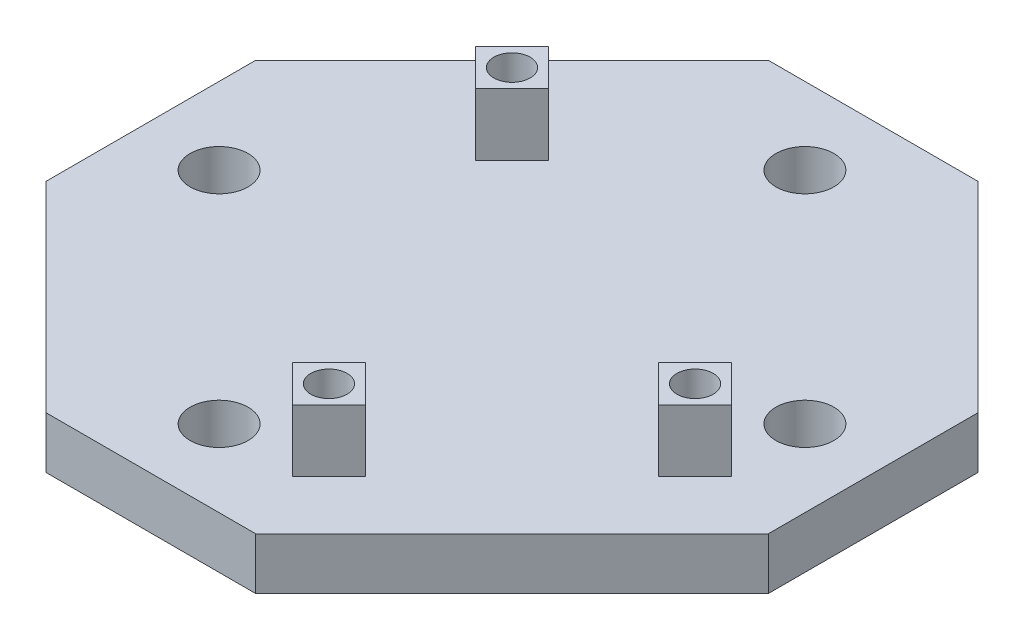
SolidWorks part; units mm, degrees
ref_plane "Front Plane" through (0, 0, 0) normal (0, 0, 1) x (1, 0, 0)
ref_plane "Top Plane" through (0, 0, 0) normal (0, 1, 0) x (1, 0, 0)
ref_plane "Right Plane" through (0, 0, 0) normal (1, 0, 0) x (0, 0, -1)
sketch "Sketch1" plane through (0, 0, 0) normal (0, 1, 0) x (1, 0, 0)
  line L0 (-40.3039, 15.5552) -> (-15.5552, 40.3039)
  line L1 (-40.3039, -40.3039) -> (40.3039, -40.3039) construction
  line L2 (-40.3039, -40.3039) -> (-40.3039, 40.3039) construction
  line L3 (-40.3039, 40.3039) -> (40.3039, 40.3039) construction
  line L4 (40.3039, -40.3039) -> (40.3039, 40.3039) construction
  line L5 (-40.3039, -40.3039) -> (40.3039, 40.3039) construction
  line L6 (-40.3039, 40.3039) -> (40.3039, -40.3039) construction
  line L7 (-27.9296, 27.9296) -> (2.476, -2.476) construction
  line L8 (-11.6661, -16.6182) -> (16.6182, 11.6661) construction
  line L9 (-11.6661, -16.6182) -> (-32.8793, 4.5951) construction
  line L10 (16.6182, 11.6661) -> (-4.5951, 32.8793) construction
  line L11 (-40.3039, 15.5552) -> (-40.3039, -4.6948)
  line L12 (-15.5552, 40.3039) -> (4.6948, 40.3039)
  line L13 (24.0428, 0.706) -> (24.0428, 20.956)
  line L14 (-0.706, -24.0428) -> (-20.956, -24.0428)
  line L15 (-32.8793, 4.5951) -> (-4.5951, 32.8793) construction
  line L16 (-18.7372, 18.7372) -> (11.6684, -11.6684) construction
  line L17 (-0.706, -24.0428) -> (24.0428, 0.706)
  line L18 (-40.3039, -4.6948) -> (-20.956, -24.0428)
  line L19 (4.6948, 40.3039) -> (24.0428, 20.956)
  circle A0 centre (-11.6661, -16.6182) radius 2.8
  circle A1 centre (16.6182, 11.6661) radius 2.8
  circle A2 centre (-4.5951, 32.8793) radius 2.8
  circle A3 centre (-32.8793, 4.5951) radius 2.8
  point P0 (0, 0)
  point P13 (2.476, -2.476)
  point P28 (11.6684, -11.6684)
  dimension "D6" = 5.6
  dimension "D1" = 135
  dimension "D2" = 35
  dimension "D3" = 43
  dimension "D4" = 40
  dimension "D5" = 30
  dimension "D7" = 20.25
  dimension "D8" = 20.25
  dimension "D9" = 43
  dimension "D10" = 35
  dimension "D11" = 20.25
  dimension "D12" = 20.25
extrude "Boss-Extrude1" add sketch "Sketch1" along normal blind 5
sketch "Sketch2" plane through (0, 5, 0) normal (0, 1, 0) x (1, 0, 0)
  line L0 (-27.9296, 27.9296) -> (11.6684, -11.6684) construction
  line L1 (-15.5552, 40.3039) -> (-40.3039, 15.5552) construction
  line L2 (-0.706, -24.0428) -> (24.0428, 0.706) construction
  line L3 (-18.7372, -2.476) -> (2.476, 18.7372) construction
  line L4 (-12.55, 33.7632) -> (17.502, 3.7112) construction
  line L5 (-12.55, 33.7632) -> (-33.7632, 12.55) construction
  line L6 (-33.7632, 12.55) -> (-3.7112, -17.502) construction
  line L7 (-3.7112, -17.502) -> (17.502, 3.7112) construction
  line L8 (15.7343, 5.4789) -> (13.9665, 3.7112) construction
  line L9 (13.9665, 3.7112) -> (15.7343, 1.9434) construction
  line L10 (-5.4789, -15.7343) -> (-3.7112, -13.9665) construction
  line L11 (-3.7112, -13.9665) -> (-1.9434, -15.7343) construction
  line L12 (-23.1566, 23.1566) -> (-21.3181, 21.3181) construction
  circle A0 centre (13.9665, 3.7112) radius 1.75
  circle A1 centre (-3.7112, -13.9665) radius 1.75
  circle A3 centre (-21.3181, 21.3181) radius 1.75
  point P9 (-8.1306, 8.1306)
  point P12 (2.476, 18.7372)
  dimension "D7" = 3.5
  dimension "D10" = 3.5
  dimension "D11" = 2.6
  dimension "D12" = 3.5
  dimension "D1" = 30
  dimension "D2" = 42.5
  dimension "D3" = 30
  dimension "D4" = 42.5
  dimension "D5" = 2.5
  dimension "D6" = 2.5
  dimension "D8" = 2.5
  dimension "D9" = 2.5
extrude "Cut-Extrude1" cut sketch "Sketch2" against normal blind 10 and the other way blind 16
sketch "Sketch3" plane through (0, 0, 0) normal (0, -1, 0) x (1, 0, 0)
  line L0 (-0.706, 24.0428) -> (24.0428, -0.706) construction
  line L1 (-4.5629, 10.7877) -> (-1.3842, 11.6395)
  line L2 (-1.3842, 11.6395) -> (-0.5324, 14.8182)
  line L3 (-0.5324, 14.8182) -> (-2.8594, 17.1453)
  line L4 (-2.8594, 17.1453) -> (-6.0382, 16.2935)
  line L5 (-6.0382, 16.2935) -> (-6.8899, 13.1148)
  line L6 (-6.8899, 13.1148) -> (-4.5629, 10.7877)
  line L7 (10.7877, -4.5629) -> (13.1148, -6.8899)
  line L8 (13.1148, -6.8899) -> (16.2935, -6.0382)
  line L9 (16.2935, -6.0382) -> (17.1453, -2.8594)
  line L10 (17.1453, -2.8594) -> (14.8182, -0.5324)
  line L11 (14.8182, -0.5324) -> (11.6395, -1.3842)
  line L12 (11.6395, -1.3842) -> (10.7877, -4.5629)
  line L13 (-22.1699, -24.4969) -> (-18.9911, -23.6451)
  line L14 (-18.9911, -23.6451) -> (-18.1394, -20.4664)
  line L15 (-18.1394, -20.4664) -> (-20.4664, -18.1394)
  line L16 (-20.4664, -18.1394) -> (-23.6451, -18.9911)
  line L17 (-23.6451, -18.9911) -> (-24.4969, -22.1699)
  line L18 (-24.4969, -22.1699) -> (-22.1699, -24.4969)
  line L19 (-15.5552, -40.3039) -> (-40.3039, -15.5552) construction
  circle A0 centre (-3.7112, 13.9665) radius 2.85 construction
  circle A1 centre (13.9665, -3.7112) radius 2.85 construction
  circle A2 centre (-21.3181, -21.3181) radius 2.85 construction
  dimension "D1" = 5.7
extrude "Cut-Extrude2" cut sketch "Sketch3" against normal blind 3.5
sketch "Sketch4" plane through (0, 5, 0) normal (0, 1, 0) x (1, 0, 0)
  line L0 (-5.4789, -15.7343) -> (-1.9434, -12.1987) construction
  line L1 (-0.706, -24.0428) -> (24.0428, 0.706) construction
  line L2 (-7.2467, -13.9665) -> (-3.7112, -17.502)
  line L3 (-3.7112, -10.431) -> (-0.1756, -13.9665)
  line L4 (-7.2467, -13.9665) -> (-3.7112, -10.431)
  line L5 (-3.7112, -17.502) -> (-0.1756, -13.9665)
  line L6 (-23.0859, 19.5504) -> (-19.5504, 23.0859) construction
  line L7 (-12.55, 33.7632) -> (-33.7632, 12.55) construction
  line L8 (-21.3181, 17.7826) -> (-24.8537, 21.3181)
  line L9 (-40.3039, -4.6948) -> (-20.956, -24.0428) construction
  line L10 (-17.7826, 21.3181) -> (-21.3181, 24.8537)
  line L11 (-24.8537, 21.3181) -> (-21.3181, 24.8537)
  line L12 (-21.3181, 17.7826) -> (-17.7826, 21.3181)
  line L13 (12.1987, 5.4789) -> (15.7343, 1.9434) construction
  line L14 (10.431, 3.7112) -> (13.9665, 7.2467)
  line L15 (17.502, 3.7112) -> (13.9665, 0.1756)
  line L16 (10.431, 3.7112) -> (13.9665, 0.1756)
  line L17 (13.9665, 7.2467) -> (17.502, 3.7112)
  point P4 (-3.7112, -13.9665)
  point P9 (-5.4789, -15.7343)
  point P13 (-1.9434, -12.1987)
  point P17 (-21.3181, 21.3181)
  point P22 (-23.0859, 19.5504)
  point P27 (-19.5504, 23.0859)
  point P32 (13.9665, 3.7112)
  point P36 (12.1987, 5.4789)
  point P39 (15.7343, 1.9434)
  dimension "D1" = 5
  dimension "D2" = 5
  dimension "D3" = 5
  dimension "D4" = 5
  dimension "D5" = 5
  dimension "D6" = 5
  dimension "D7" = 5
extrude "Boss-Extrude2" add sketch "Sketch4" along normal blind 6
sketch "Sketch5" plane through (0, 5, 0) normal (0, -1, 0) x (1, 0, 0)
  circle A0 centre (-21.3181, -21.3181) radius 1.75
  circle A1 centre (-3.7112, 13.9665) radius 1.75
  circle A2 centre (13.9665, -3.7112) radius 1.75
extrude "Cut-Extrude3" cut sketch "Sketch5" against normal through all
